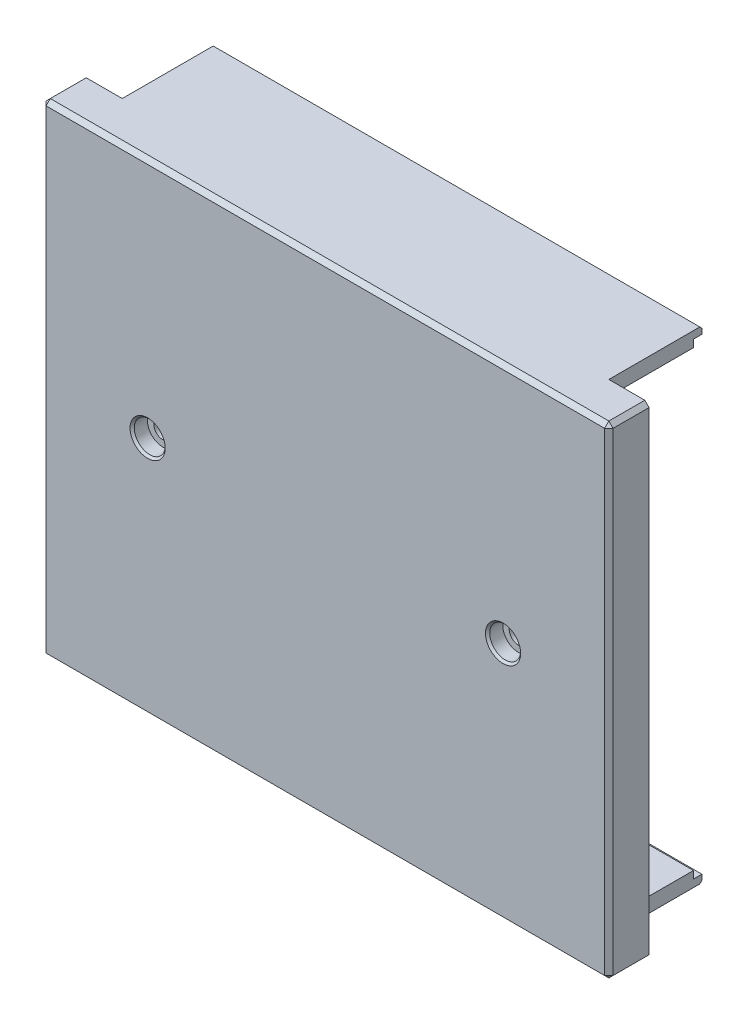
SolidWorks part; units mm, degrees
ref_plane "Front Plane" through (0, 0, 0) normal (0, 0, 1) x (1, 0, 0)
ref_plane "Top Plane" through (0, 0, 0) normal (0, 1, 0) x (1, 0, 0)
ref_plane "Right Plane" through (0, 0, 0) normal (1, 0, 0) x (0, 0, -1)
sketch "Sketch1" plane through (0, 0, 0) normal (0, 0, 1) x (1, 0, 0)
  line L1 (0, 0) -> (134, 0)
  line L2 (0, 0) -> (0, 114)
  line L3 (0, 114) -> (134, 114)
  line L4 (134, 0) -> (134, 114)
  dimension "D1" = 134
  dimension "D2" = 114
extrude "Boss-Extrude1" add sketch "Sketch1" along normal blind 9.5
sketch "Sketch2" plane through (0, 0, 0) normal (0, 0, -1) x (-1, 0, 0)
  line L0 (-67, 114) -> (-67, 0) construction
  line L1 (-134, 114) -> (0, 114) construction
  line L2 (0, 0) -> (-134, 0) construction
  line L3 (-67, 114) -> (-124.5, 114)
  line L4 (-124.5, 114) -> (-124.5, 110.5)
  line L5 (-124.5, 110.5) -> (-9.5, 110.5)
  line L6 (-9.5, 110.5) -> (-9.5, 114)
  line L7 (-9.5, 114) -> (-67, 114)
  line L9 (-124.5, 0) -> (-9.5, 0)
  line L10 (-124.5, 0) -> (-124.5, 3.5)
  line L11 (-124.5, 3.5) -> (-9.5, 3.5)
  line L12 (-9.5, 0) -> (-9.5, 3.5)
  dimension "D1" = 3.5
  dimension "D2" = 115
extrude "Boss-Extrude2" add sketch "Sketch2" along normal blind 20
sketch "Sketch3" plane through (0, 0, 9.5) normal (0, 0, 1) x (1, 0, 0)
  line L0 (0, 57) -> (134, 57) construction
  line L1 (0, 114) -> (0, 0) construction
  line L2 (134, 0) -> (134, 114) construction
  circle A0 centre (25, 57) radius 2.15
  circle A1 centre (109, 57) radius 2.15
  dimension "D1" = 4.3
  dimension "D3" = 25
  dimension "D2" = 25
extrude "Cut-Extrude1" cut sketch "Sketch3" against normal through all
sketch "Sketch4" plane through (0, 0, 9.5) normal (0, 0, 1) x (1, 0, 0)
  circle A0 centre (25, 57) radius 3.65
  circle A1 centre (109, 57) radius 3.65
  dimension "D1" = 7.3
extrude "Cut-Extrude2" cut sketch "Sketch4" against normal blind 3.6
chamfer "Chamfer1" distance 1 angle 45 8 edges at (0, 0, 4.75) (0, 114, 4.75) (134, 114, 4.75) (134, 0, 4.75) (134, 57, 9.5) (67, 0, 9.5) (0, 57, 9.5) (67, 114, 9.5)
chamfer "Chamfer4" distance 0.5 angle 45 2 edges at (112.65, 57, 9.5) (28.65, 57, 9.5)
sketch "Sketch5" plane through (0, 0, -20) normal (0, 0, -1) x (-1, 0, 0)
  line L0 (-9.5, 110.5) -> (-9.5, 114) construction
  line L1 (-124.5, 114) -> (-9.5, 114)
  line L2 (-124.5, 114) -> (-124.5, 112.25)
  line L3 (-124.5, 112.25) -> (-9.5, 112.25)
  line L4 (-9.5, 114) -> (-9.5, 112.25)
  line L5 (-9.5, 0) -> (-9.5, 3.5) construction
  line L6 (-124.5, 0) -> (-9.5, 0)
  line L7 (-124.5, 0) -> (-124.5, 1.75)
  line L8 (-124.5, 1.75) -> (-9.5, 1.75)
  line L9 (-9.5, 0) -> (-9.5, 1.75)
extrude "Boss-Extrude3" add sketch "Sketch5" along normal blind 2
chamfer "Chamfer5" distance 0.5 angle 45 2 edges at (67, 0, -22) (67, 114, -22)
